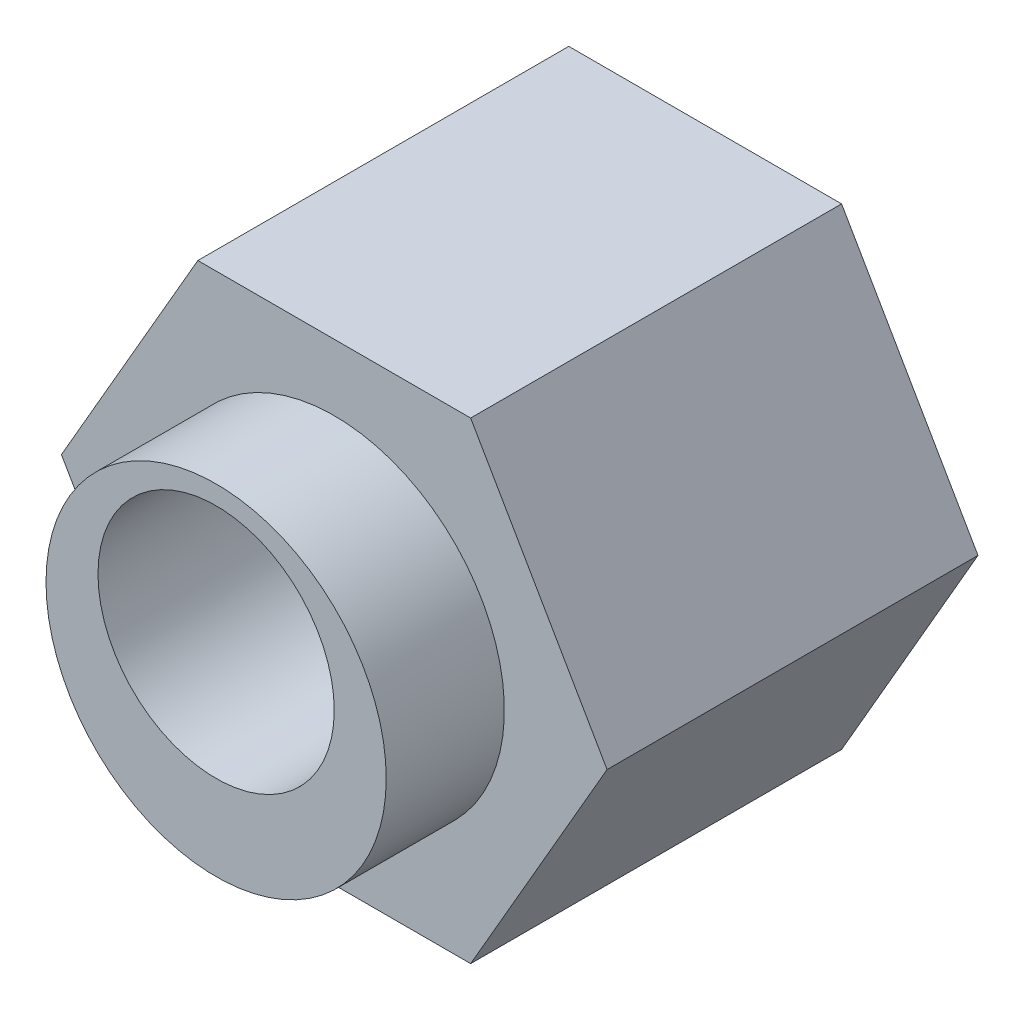
SolidWorks part; units mm, degrees
material "3.0205 (EN-AW 1200)"
ref_plane "Alzado" through (0, 0, 0) normal (0, 0, 1) x (1, 0, 0)
ref_plane "Planta" through (0, 0, 0) normal (0, 1, 0) x (1, 0, 0)
ref_plane "Vista lateral" through (0, 0, 0) normal (1, 0, 0) x (0, 0, -1)
ref_plane "Plano1" through (0, 0, 0.45) normal (0, 0, -1) x (-1, 0, 0)
sketch "Croquis1" plane through (0, 0, 0.45) normal (0, 0, -1) x (-1, 0, 0)
  line L0 (2.8868, -5) -> (5.7735, 0)
  line L1 (5.7735, 0) -> (2.8868, 5)
  line L2 (2.8868, 5) -> (-2.8868, 5)
  line L3 (-2.8868, 5) -> (-5.7735, 0)
  line L4 (-5.7735, 0) -> (-2.8868, -5)
  line L5 (-2.8868, -5) -> (2.8868, -5)
extrude "Saliente-Extruir1" add sketch "Croquis1" against normal blind 7.85
sketch "Croquis6" plane through (0, 0, 8.3) normal (0, 0, 1) x (1, 0, 0)
  circle A0 centre (0, 0) radius 3.6
  circle A1 centre (0, 0.7) radius 2.5
ref_plane "Plano4" through (0, 0, 0.45) normal (0, 0, -1) x (-1, 0, 0)
sketch "Croquis7" plane through (0, 0, 0.45) normal (0, 0, -1) x (-1, 0, 0)
  circle A0 centre (0, 0) radius 3.6
  circle A1 centre (0, 0.7) radius 2.5
extrude "Saliente-Extruir2" add sketch "Croquis6" along normal blind 2.5
extrude "Saliente-Extruir3" add sketch "Croquis7" along normal blind 0.5
sketch "Croquis9" plane through (0, 0, 8.3) normal (0, 0, 1) x (1, 0, 0)
  circle A0 centre (0, 0.7) radius 2.5
extrude "Cortar-Extruir1" cut sketch "Croquis9" against normal blind 8.5
